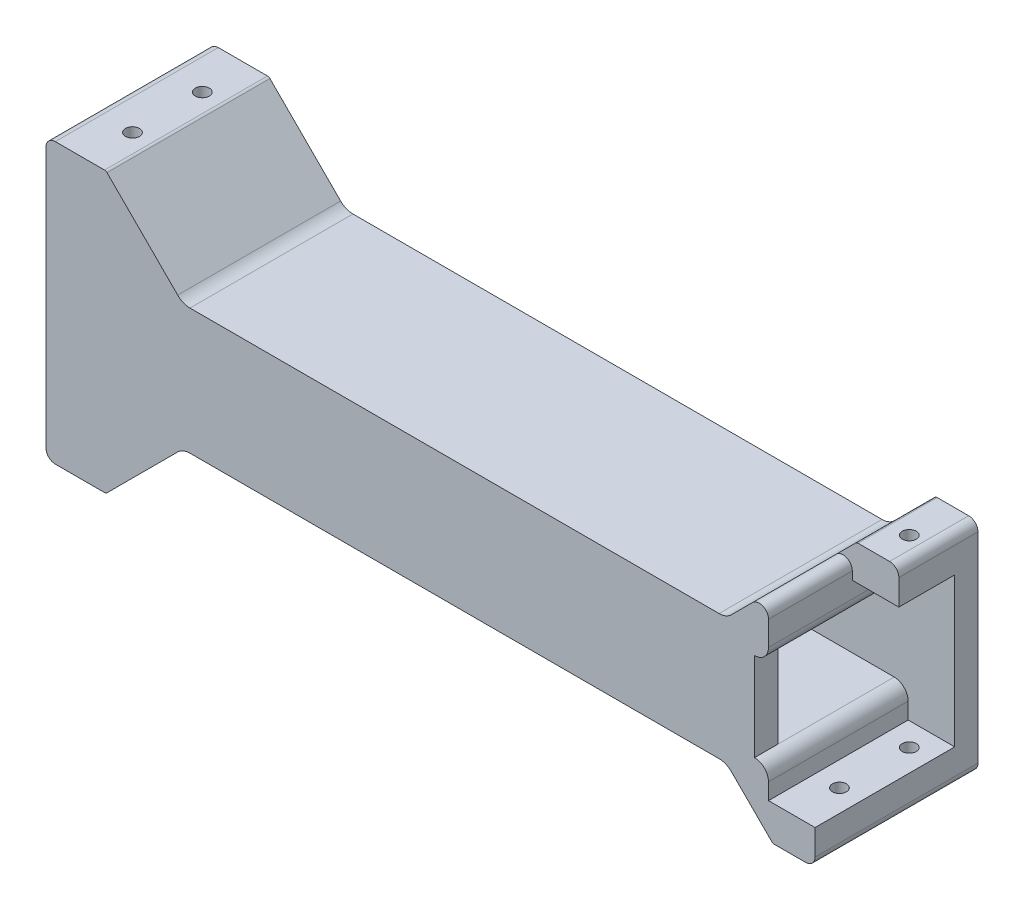
SolidWorks part; units mm, degrees
ref_plane "前视基准面" through (0, 0, 0) normal (0, 0, 1) x (1, 0, 0)
ref_plane "上视基准面" through (0, 0, 0) normal (0, 1, 0) x (1, 0, 0)
ref_plane "右视基准面" through (0, 0, 0) normal (1, 0, 0) x (0, 0, -1)
other "Configuration Table"
sketch "草图1" plane through (0, 0, 0) normal (0, 0, 1) x (1, 0, 0)
  line L43 (27.6425, 62.7843) -> (42.8324, 47.5944)
  line L44 (42.8324, 47.5944) -> (44.9537, 49.7157)
  line L45 (44.9537, 49.7157) -> (29.7639, 64.9056)
  line L46 (27.1217, 66) -> (-22.1169, 66)
  line L47 (-22.1169, 66) -> (-22.1169, 63)
  line L48 (-22.1169, 63) -> (27.1217, 63)
  line L49 (27.1217, 3) -> (-22.1169, 3)
  line L50 (-22.1169, 3) -> (-22.1169, 0)
  line L51 (-22.1169, 0) -> (27.1217, 0)
  line L52 (29.7639, 1.0944) -> (44.9537, 16.2843)
  line L53 (44.9537, 16.2843) -> (42.8324, 18.4056)
  line L54 (42.8324, 18.4056) -> (27.6425, 3.2157)
  line L55 (159.1217, 49.5) -> (45.4745, 49.5)
  line L56 (45.4745, 49.5) -> (45.4745, 46.5)
  line L57 (45.4745, 46.5) -> (159.1217, 46.5)
  line L58 (168.3324, 58.4056) -> (159.6425, 49.7157)
  line L59 (161.7639, 47.5944) -> (170.4537, 56.2843)
  line L60 (170.9745, 56.5) -> (183.3346, 56.5)
  line L61 (183.3346, 56.5) -> (183.3346, 59.5)
  line L62 (183.3346, 59.5) -> (170.9745, 59.5)
  line L63 (170.9745, 6.5) -> (183.3346, 6.5)
  line L64 (183.3346, 6.5) -> (183.3346, 9.5)
  line L65 (183.3346, 9.5) -> (170.9745, 9.5)
  line L66 (159.1217, 19.5) -> (45.4745, 19.5)
  line L67 (45.4745, 19.5) -> (45.4745, 16.5)
  line L68 (45.4745, 16.5) -> (159.1217, 16.5)
  line L69 (170.4537, 9.7157) -> (161.7639, 18.4056)
  line L70 (159.6425, 16.2843) -> (168.3324, 7.5944)
  line L71 (14.5441, 63) -> (14.5441, 3)
  line L72 (179.7384, 56.5) -> (179.7384, 9.5)
  line L79 (168.3324, 7.5944) -> (170.4537, 9.7157)
  line L80 (170.4537, 9.7157) -> (161.7639, 18.4056)
  line L81 (161.7639, 18.4056) -> (159.6425, 16.2843)
  line L82 (159.6425, 16.2843) -> (168.3324, 7.5944)
  arc A14 (27.6425, 62.7843) -> (27.1217, 63) centre (27.1217, 62.2634) ccw
  arc A15 (29.7639, 64.9056) -> (27.1217, 66) centre (27.1217, 62.2634) ccw
  arc A16 (27.1217, 0) -> (29.7639, 1.0944) centre (27.1217, 3.7366) ccw
  arc A17 (27.1217, 3) -> (27.6425, 3.2157) centre (27.1217, 3.7366) ccw
  arc A18 (159.1217, 46.5) -> (161.7639, 47.5944) centre (159.1217, 50.2366) ccw
  arc A19 (159.1217, 49.5) -> (159.6425, 49.7157) centre (159.1217, 50.2366) ccw
  arc A20 (170.9745, 56.5) -> (170.4537, 56.2843) centre (170.9745, 55.7634) ccw
  arc A21 (170.9745, 59.5) -> (168.3324, 58.4056) centre (170.9745, 55.7634) ccw
  arc A22 (168.3324, 7.5944) -> (170.9745, 6.5) centre (170.9745, 10.2366) ccw
  arc A23 (170.4537, 9.7157) -> (170.9745, 9.5) centre (170.9745, 10.2366) ccw
  arc A24 (159.6425, 16.2843) -> (159.1217, 16.5) centre (159.1217, 15.7634) ccw
  arc A25 (161.7639, 18.4056) -> (159.1217, 19.5) centre (159.1217, 15.7634) ccw
  arc A26 (45.4745, 19.5) -> (42.8324, 18.4056) centre (45.4745, 15.7634) ccw
  arc A27 (45.4745, 16.5) -> (44.9537, 16.2843) centre (45.4745, 15.7634) ccw
  arc A28 (45.4745, 49.5) -> (44.9537, 49.7157) centre (45.4745, 50.2366) cw
  arc A29 (45.4745, 46.5) -> (42.8324, 47.5944) centre (45.4745, 50.2366) cw
extrude "凸台-拉伸1" add sketch "草图1" along normal blind 35 contours L57 A29 L43 A14 L48 L71 L49 A17 L54 A26 L66 A25 L69 A23 L65 L72 L60 A20 L59 A18
sketch "草图3" plane through (14.5441, 0, 0) normal (-1, 0, 0) x (0, 0, 1)
  line L0 (35, 46.5) -> (0, 46.5) construction
  line L1 (35, 19.5) -> (0, 19.5) construction
  line L2 (35, 46.5) -> (0, 46.5) construction
  line L3 (35, 19.5) -> (0, 19.5) construction
  line L4 (0, 46.5) -> (35, 19.5) construction
  line L5 (35, 46.5) -> (0, 19.5) construction
  line L6 (35, 63) -> (35, 3) construction
  line L7 (5, 42.5) -> (30, 42.5)
  line L8 (5, 42.5) -> (5, 23.5)
  line L9 (5, 23.5) -> (30, 23.5)
  line L10 (30, 42.5) -> (30, 23.5)
  line L11 (5, 42.5) -> (30, 23.5) construction
  line L12 (5, 23.5) -> (30, 42.5) construction
  point P4 (17.5, 33)
  dimension "D1" = 5
  dimension "D2" = 4
extrude "切除-拉伸1" cut sketch "草图3" against normal through all
sketch "草图4" plane through (14.5441, 0, 0) normal (-1, 0, 0) x (0, 0, 1)
  line L18 (0, 63) -> (0, 3)
  line L19 (0, 3) -> (35, 3)
  line L20 (35, 3) -> (35, 63)
  line L39 (35, 63) -> (0, 63)
  line L40 (0, 63) -> (0, 3)
  line L41 (0, 3) -> (35, 3)
  line L42 (35, 3) -> (35, 63)
  line L43 (35, 63) -> (0, 63)
  line L44 (5, 55) -> (30, 55)
  line L45 (5, 11) -> (30, 11)
  line L48 (5, 58) -> (5, 8)
  line L49 (5, 8) -> (30, 8)
  line L50 (30, 8) -> (30, 58)
  line L51 (30, 58) -> (5, 58)
  line L52 (5, 58) -> (5, 8)
  line L53 (5, 8) -> (30, 8)
  line L54 (30, 8) -> (30, 58)
  line L55 (30, 58) -> (5, 58)
  dimension "D3" = 3
  dimension "D4" = 3
  dimension "D1" = 0
  dimension "D2" = 5
extrude "切除-拉伸2" cut sketch "草图4" against normal blind 13.5
sketch "草图5" plane through (179.7384, 0, 0) normal (1, 0, 0) x (0, 0, -1)
  line L0 (-35, 56.5) -> (0, 9.5) construction
  line L1 (-35, 9.5) -> (0, 56.5) construction
  line L4 (-30, 49) -> (-5, 49)
  line L5 (0, 9.5) -> (0, 56.5)
  line L7 (0, 56.5) -> (-35, 56.5)
  line L16 (-35, 56.5) -> (-35, 9.5)
  line L18 (-35, 9.5) -> (0, 9.5)
  line L19 (0, 9.5) -> (0, 56.5) construction
  line L20 (0, 56.5) -> (-35, 56.5) construction
  line L23 (-35, 56.5) -> (-35, 9.5) construction
  line L24 (-35, 9.5) -> (0, 9.5) construction
  line L25 (-30, 49) -> (-30, 17)
  line L26 (-30, 17) -> (-5, 17)
  line L27 (-5, 49) -> (-5, 17)
  line L28 (-30, 49) -> (-5, 17) construction
  line L29 (-30, 17) -> (-5, 49) construction
  point P2 (-17.5, 33)
  dimension "D2" = 25
  dimension "D3" = 32
  dimension "D1" = 0
extrude "切除-拉伸3" cut sketch "草图5" against normal blind 10
fillet "圆角1" radius 3 4 edges at (169.7384, 23.5, 17.5) (169.7384, 42.5, 17.5) (28.0441, 42.5, 17.5) (28.0441, 23.5, 17.5)
fillet "圆角2" radius 2 4 edges at (179.7384, 56.5, 17.5) (179.7384, 9.5, 17.5) (14.5441, 63, 17.5) (14.5441, 3, 17.5)
sketch "草图6" plane through (0, 55, 0) normal (0, -1, 0) x (1, 0, 0)
  circle A0 centre (23.1217, 25) radius 1.5 construction
  circle A1 centre (23.1217, 25) radius 1.5
  circle A2 centre (23.1217, 10) radius 1.5 construction
  circle A3 centre (23.1217, 10) radius 1.5
extrude "切除-拉伸4" cut sketch "草图6" against normal through all and the other way through all
sketch "草图7" plane through (0, 49, 0) normal (0, -1, 0) x (1, 0, 0)
  circle A0 centre (174.9745, 25) radius 1.5 construction
  circle A1 centre (174.9745, 10) radius 1.5 construction
  circle A2 centre (174.9745, 25) radius 1.5
  circle A3 centre (174.9745, 10) radius 1.5
extrude "切除-拉伸5" cut sketch "草图7" against normal through all and the other way through all
sketch "草图8" plane through (0, 0, 5) normal (0, 0, 1) x (1, 0, 0)
  line L0 (28.0441, 45.5) -> (28.0441, 20.5)
  line L1 (169.7384, 45.5) -> (169.7384, 20.5)
  line L12 (179.7384, 17) -> (179.7384, 49)
  line L13 (179.7384, 49) -> (169.7384, 49)
  line L14 (169.7384, 49) -> (169.7384, 45.5)
  line L15 (166.7384, 42.5) -> (31.0441, 42.5)
  line L16 (28.0441, 45.5) -> (28.0441, 55)
  line L17 (28.0441, 55) -> (14.5441, 55)
  line L18 (14.5441, 55) -> (14.5441, 11)
  line L19 (14.5441, 11) -> (28.0441, 11)
  line L20 (28.0441, 11) -> (28.0441, 20.5)
  line L21 (31.0441, 23.5) -> (166.7384, 23.5)
  line L22 (169.7384, 20.5) -> (169.7384, 17)
  line L23 (169.7384, 17) -> (179.7384, 17)
  line L24 (179.7384, 17) -> (179.7384, 49)
  line L25 (179.7384, 49) -> (169.7384, 49)
  line L26 (169.7384, 49) -> (169.7384, 45.5)
  line L27 (166.7384, 42.5) -> (31.0441, 42.5)
  line L28 (28.0441, 45.5) -> (28.0441, 55)
  line L29 (28.0441, 55) -> (14.5441, 55)
  line L30 (14.5441, 55) -> (14.5441, 11)
  line L31 (14.5441, 11) -> (28.0441, 11)
  line L32 (28.0441, 11) -> (28.0441, 20.5)
  line L33 (31.0441, 23.5) -> (166.7384, 23.5)
  line L34 (169.7384, 20.5) -> (169.7384, 17)
  line L35 (169.7384, 17) -> (179.7384, 17)
  arc A4 (166.7384, 42.5) -> (169.7384, 45.5) centre (166.7384, 45.5) ccw
  arc A5 (28.0441, 45.5) -> (31.0441, 42.5) centre (31.0441, 45.5) ccw
  arc A6 (31.0441, 23.5) -> (28.0441, 20.5) centre (31.0441, 20.5) ccw
  arc A7 (169.7384, 20.5) -> (166.7384, 23.5) centre (166.7384, 20.5) ccw
  arc A8 (166.7384, 42.5) -> (169.7384, 45.5) centre (166.7384, 45.5) ccw
  arc A9 (28.0441, 45.5) -> (31.0441, 42.5) centre (31.0441, 45.5) ccw
  arc A10 (31.0441, 23.5) -> (28.0441, 20.5) centre (31.0441, 20.5) ccw
  arc A11 (169.7384, 20.5) -> (166.7384, 23.5) centre (166.7384, 20.5) ccw
  dimension "D1" = 0
extrude "切除-拉伸6" cut sketch "草图8" against normal through all
sketch "草图9" plane through (0, 0, 30) normal (0, 0, -1) x (-1, 0, 0)
  line L0 (-179.7384, 49) -> (-179.7384, 17)
  line L20 (-179.7384, 54.5) -> (-179.7384, 49)
  line L21 (-179.7384, 49) -> (-169.7384, 49)
  line L22 (-169.7384, 49) -> (-169.7384, 17)
  line L23 (-169.7384, 17) -> (-179.7384, 17)
  line L24 (-179.7384, 17) -> (-179.7384, 11.5)
  line L25 (-177.7384, 9.5) -> (-170.9745, 9.5)
  line L26 (-170.4537, 9.7157) -> (-161.7639, 18.4056)
  line L27 (-159.1217, 19.5) -> (-45.4745, 19.5)
  line L28 (-42.8324, 18.4056) -> (-27.6425, 3.2157)
  line L29 (-27.1217, 3) -> (-16.5441, 3)
  line L30 (-14.5441, 5) -> (-14.5441, 11)
  line L31 (-14.5441, 11) -> (-28.0441, 11)
  line L32 (-28.0441, 11) -> (-28.0441, 55)
  line L33 (-28.0441, 55) -> (-14.5441, 55)
  line L34 (-14.5441, 55) -> (-14.5441, 61)
  line L35 (-16.5441, 63) -> (-27.1217, 63)
  line L36 (-27.6425, 62.7843) -> (-42.8324, 47.5944)
  line L37 (-45.4745, 46.5) -> (-159.1217, 46.5)
  line L38 (-161.7639, 47.5944) -> (-170.4537, 56.2843)
  line L39 (-170.9745, 56.5) -> (-177.7384, 56.5)
  line L40 (-179.7384, 54.5) -> (-179.7384, 49)
  line L41 (-179.7384, 49) -> (-169.7384, 49)
  line L42 (-169.7384, 49) -> (-169.7384, 17)
  line L43 (-169.7384, 17) -> (-179.7384, 17)
  line L44 (-179.7384, 17) -> (-179.7384, 11.5)
  line L45 (-177.7384, 9.5) -> (-170.9745, 9.5)
  line L46 (-170.4537, 9.7157) -> (-161.7639, 18.4056)
  line L47 (-159.1217, 19.5) -> (-45.4745, 19.5)
  line L48 (-42.8324, 18.4056) -> (-27.6425, 3.2157)
  line L49 (-27.1217, 3) -> (-16.5441, 3)
  line L50 (-14.5441, 5) -> (-14.5441, 11)
  line L51 (-14.5441, 11) -> (-28.0441, 11)
  line L52 (-28.0441, 11) -> (-28.0441, 55)
  line L53 (-28.0441, 55) -> (-14.5441, 55)
  line L54 (-14.5441, 55) -> (-14.5441, 61)
  line L55 (-16.5441, 63) -> (-27.1217, 63)
  line L56 (-27.6425, 62.7843) -> (-42.8324, 47.5944)
  line L57 (-45.4745, 46.5) -> (-159.1217, 46.5)
  line L58 (-161.7639, 47.5944) -> (-170.4537, 56.2843)
  line L59 (-170.9745, 56.5) -> (-177.7384, 56.5)
  arc A12 (-179.7384, 11.5) -> (-177.7384, 9.5) centre (-177.7384, 11.5) ccw
  arc A13 (-170.9745, 9.5) -> (-170.4537, 9.7157) centre (-170.9745, 10.2366) ccw
  arc A14 (-159.1217, 19.5) -> (-161.7639, 18.4056) centre (-159.1217, 15.7634) ccw
  arc A15 (-42.8324, 18.4056) -> (-45.4745, 19.5) centre (-45.4745, 15.7634) ccw
  arc A16 (-27.6425, 3.2157) -> (-27.1217, 3) centre (-27.1217, 3.7366) ccw
  arc A17 (-16.5441, 3) -> (-14.5441, 5) centre (-16.5441, 5) ccw
  arc A18 (-14.5441, 61) -> (-16.5441, 63) centre (-16.5441, 61) ccw
  arc A19 (-27.1217, 63) -> (-27.6425, 62.7843) centre (-27.1217, 62.2634) ccw
  arc A20 (-45.4745, 46.5) -> (-42.8324, 47.5944) centre (-45.4745, 50.2366) ccw
  arc A21 (-161.7639, 47.5944) -> (-159.1217, 46.5) centre (-159.1217, 50.2366) ccw
  arc A22 (-170.4537, 56.2843) -> (-170.9745, 56.5) centre (-170.9745, 55.7634) ccw
  arc A23 (-177.7384, 56.5) -> (-179.7384, 54.5) centre (-177.7384, 54.5) ccw
  arc A24 (-179.7384, 11.5) -> (-177.7384, 9.5) centre (-177.7384, 11.5) ccw
  arc A25 (-170.9745, 9.5) -> (-170.4537, 9.7157) centre (-170.9745, 10.2366) ccw
  arc A26 (-159.1217, 19.5) -> (-161.7639, 18.4056) centre (-159.1217, 15.7634) ccw
  arc A27 (-42.8324, 18.4056) -> (-45.4745, 19.5) centre (-45.4745, 15.7634) ccw
  arc A28 (-27.6425, 3.2157) -> (-27.1217, 3) centre (-27.1217, 3.7366) ccw
  arc A29 (-16.5441, 3) -> (-14.5441, 5) centre (-16.5441, 5) ccw
  arc A30 (-14.5441, 61) -> (-16.5441, 63) centre (-16.5441, 61) ccw
  arc A31 (-27.1217, 63) -> (-27.6425, 62.7843) centre (-27.1217, 62.2634) ccw
  arc A32 (-45.4745, 46.5) -> (-42.8324, 47.5944) centre (-45.4745, 50.2366) ccw
  arc A33 (-161.7639, 47.5944) -> (-159.1217, 46.5) centre (-159.1217, 50.2366) ccw
  arc A34 (-170.4537, 56.2843) -> (-170.9745, 56.5) centre (-170.9745, 55.7634) ccw
  arc A35 (-177.7384, 56.5) -> (-179.7384, 54.5) centre (-177.7384, 54.5) ccw
  line M33 (-179.7384, 49) -> (-179.7384, 17)
  line M34 (-179.7384, 17) -> (-169.7384, 17)
  line M35 (-169.7384, 17) -> (-169.7384, 20.5)
  line M47 (-169.7384, 45.5) -> (-169.7384, 49)
  line M48 (-169.7384, 49) -> (-179.7384, 49)
  dimension "D1" = 0
extrude "切除-拉伸7" cut sketch "草图9" against normal blind 10 contours L42 M47 M48 M33 M34 M35
sketch "草图10" plane through (0, 0, 35) normal (0, 0, 1) x (1, 0, 0)
  line L0 (169.7384, 49) -> (169.7384, 55.569)
  line L16 (179.7384, 17) -> (169.7384, 17)
  line L17 (169.7384, 17) -> (169.7384, 49)
  line L18 (169.7384, 49) -> (179.7384, 49)
  line L19 (179.7384, 49) -> (179.7384, 54.5)
  line L20 (177.7384, 56.5) -> (170.9745, 56.5)
  line L21 (170.4537, 56.2843) -> (161.7639, 47.5944)
  line L22 (159.1217, 46.5) -> (45.4745, 46.5)
  line L23 (42.8324, 47.5944) -> (27.6425, 62.7843)
  line L24 (27.1217, 63) -> (16.5441, 63)
  line L25 (14.5441, 61) -> (14.5441, 5)
  line L26 (16.5441, 3) -> (27.1217, 3)
  line L27 (27.6425, 3.2157) -> (42.8324, 18.4056)
  line L28 (45.4745, 19.5) -> (159.1217, 19.5)
  line L29 (161.7639, 18.4056) -> (170.4537, 9.7157)
  line L30 (170.9745, 9.5) -> (177.7384, 9.5)
  line L31 (179.7384, 11.5) -> (179.7384, 17)
  line L32 (179.7384, 17) -> (169.7384, 17)
  line L33 (169.7384, 17) -> (169.7384, 49)
  line L34 (169.7384, 49) -> (179.7384, 49)
  line L35 (179.7384, 49) -> (179.7384, 54.5)
  line L36 (177.7384, 56.5) -> (170.9745, 56.5)
  line L37 (170.4537, 56.2843) -> (161.7639, 47.5944)
  line L38 (159.1217, 46.5) -> (45.4745, 46.5)
  line L39 (42.8324, 47.5944) -> (27.6425, 62.7843)
  line L40 (27.1217, 63) -> (16.5441, 63)
  line L41 (14.5441, 61) -> (14.5441, 5)
  line L42 (16.5441, 3) -> (27.1217, 3)
  line L43 (27.6425, 3.2157) -> (42.8324, 18.4056)
  line L44 (45.4745, 19.5) -> (159.1217, 19.5)
  line L45 (161.7639, 18.4056) -> (170.4537, 9.7157)
  line L46 (170.9745, 9.5) -> (177.7384, 9.5)
  line L47 (179.7384, 11.5) -> (179.7384, 17)
  arc A12 (179.7384, 54.5) -> (177.7384, 56.5) centre (177.7384, 54.5) ccw
  arc A13 (170.9745, 56.5) -> (170.4537, 56.2843) centre (170.9745, 55.7634) ccw
  arc A14 (159.1217, 46.5) -> (161.7639, 47.5944) centre (159.1217, 50.2366) ccw
  arc A15 (42.8324, 47.5944) -> (45.4745, 46.5) centre (45.4745, 50.2366) ccw
  arc A16 (27.6425, 62.7843) -> (27.1217, 63) centre (27.1217, 62.2634) ccw
  arc A17 (16.5441, 63) -> (14.5441, 61) centre (16.5441, 61) ccw
  arc A18 (14.5441, 5) -> (16.5441, 3) centre (16.5441, 5) ccw
  arc A19 (27.1217, 3) -> (27.6425, 3.2157) centre (27.1217, 3.7366) ccw
  arc A20 (45.4745, 19.5) -> (42.8324, 18.4056) centre (45.4745, 15.7634) ccw
  arc A21 (161.7639, 18.4056) -> (159.1217, 19.5) centre (159.1217, 15.7634) ccw
  arc A22 (170.4537, 9.7157) -> (170.9745, 9.5) centre (170.9745, 10.2366) ccw
  arc A23 (177.7384, 9.5) -> (179.7384, 11.5) centre (177.7384, 11.5) ccw
  arc A24 (179.7384, 54.5) -> (177.7384, 56.5) centre (177.7384, 54.5) ccw
  arc A25 (170.9745, 56.5) -> (170.4537, 56.2843) centre (170.9745, 55.7634) ccw
  arc A26 (159.1217, 46.5) -> (161.7639, 47.5944) centre (159.1217, 50.2366) ccw
  arc A27 (42.8324, 47.5944) -> (45.4745, 46.5) centre (45.4745, 50.2366) ccw
  arc A28 (27.6425, 62.7843) -> (27.1217, 63) centre (27.1217, 62.2634) ccw
  arc A29 (16.5441, 63) -> (14.5441, 61) centre (16.5441, 61) ccw
  arc A30 (14.5441, 5) -> (16.5441, 3) centre (16.5441, 5) ccw
  arc A31 (27.1217, 3) -> (27.6425, 3.2157) centre (27.1217, 3.7366) ccw
  arc A32 (45.4745, 19.5) -> (42.8324, 18.4056) centre (45.4745, 15.7634) ccw
  arc A33 (161.7639, 18.4056) -> (159.1217, 19.5) centre (159.1217, 15.7634) ccw
  arc A34 (170.4537, 9.7157) -> (170.9745, 9.5) centre (170.9745, 10.2366) ccw
  arc A35 (177.7384, 9.5) -> (179.7384, 11.5) centre (177.7384, 11.5) ccw
  line M31 (169.7384, 49) -> (179.7384, 49)
  line M32 (179.7384, 49) -> (179.7384, 54.5)
  arc M33 (179.7384, 54.5) -> (177.7384, 56.5) centre (177.7384, 54.5) ccw
  line M34 (177.7384, 56.5) -> (170.9745, 56.5)
  arc M35 (170.9745, 56.5) -> (170.4537, 56.2843) centre (170.9745, 55.7634) ccw
  line M36 (170.4537, 56.2843) -> (161.7639, 47.5944)
  dimension "D1" = 0
extrude "切除-拉伸8" cut sketch "草图10" against normal blind 18 contours L0 M31 M32 M33 M34 M35 M36
fillet "圆角3" radius 2 1 edges at (169.7384, 55.569, 26)
sketch "草图11" plane through (0, 0, 0) normal (0, 0, -1) x (-1, 0, 0)
  line L0 (-179.7384, 49) -> (-179.7384, 17)
  line L20 (-179.7384, 54.5) -> (-179.7384, 49)
  line L21 (-179.7384, 49) -> (-169.7384, 49)
  line L22 (-169.7384, 49) -> (-169.7384, 17)
  line L23 (-169.7384, 17) -> (-179.7384, 17)
  line L24 (-179.7384, 17) -> (-179.7384, 11.5)
  line L25 (-177.7384, 9.5) -> (-170.9745, 9.5)
  line L26 (-170.4537, 9.7157) -> (-161.7639, 18.4056)
  line L27 (-159.1217, 19.5) -> (-45.4745, 19.5)
  line L28 (-42.8324, 18.4056) -> (-27.6425, 3.2157)
  line L29 (-27.1217, 3) -> (-16.5441, 3)
  line L30 (-14.5441, 5) -> (-14.5441, 11)
  line L31 (-14.5441, 11) -> (-28.0441, 11)
  line L32 (-28.0441, 11) -> (-28.0441, 55)
  line L33 (-28.0441, 55) -> (-14.5441, 55)
  line L34 (-14.5441, 55) -> (-14.5441, 61)
  line L35 (-16.5441, 63) -> (-27.1217, 63)
  line L36 (-27.6425, 62.7843) -> (-42.8324, 47.5944)
  line L37 (-45.4745, 46.5) -> (-159.1217, 46.5)
  line L38 (-161.7639, 47.5944) -> (-170.4537, 56.2843)
  line L39 (-170.9745, 56.5) -> (-177.7384, 56.5)
  line L40 (-179.7384, 54.5) -> (-179.7384, 49)
  line L41 (-179.7384, 49) -> (-169.7384, 49)
  line L42 (-169.7384, 49) -> (-169.7384, 17)
  line L43 (-169.7384, 17) -> (-179.7384, 17)
  line L44 (-179.7384, 17) -> (-179.7384, 11.5)
  line L45 (-177.7384, 9.5) -> (-170.9745, 9.5)
  line L46 (-170.4537, 9.7157) -> (-161.7639, 18.4056)
  line L47 (-159.1217, 19.5) -> (-45.4745, 19.5)
  line L48 (-42.8324, 18.4056) -> (-27.6425, 3.2157)
  line L49 (-27.1217, 3) -> (-16.5441, 3)
  line L50 (-14.5441, 5) -> (-14.5441, 11)
  line L51 (-14.5441, 11) -> (-28.0441, 11)
  line L52 (-28.0441, 11) -> (-28.0441, 55)
  line L53 (-28.0441, 55) -> (-14.5441, 55)
  line L54 (-14.5441, 55) -> (-14.5441, 61)
  line L55 (-16.5441, 63) -> (-27.1217, 63)
  line L56 (-27.6425, 62.7843) -> (-42.8324, 47.5944)
  line L57 (-45.4745, 46.5) -> (-159.1217, 46.5)
  line L58 (-161.7639, 47.5944) -> (-170.4537, 56.2843)
  line L59 (-170.9745, 56.5) -> (-177.7384, 56.5)
  arc A12 (-179.7384, 11.5) -> (-177.7384, 9.5) centre (-177.7384, 11.5) ccw
  arc A13 (-170.9745, 9.5) -> (-170.4537, 9.7157) centre (-170.9745, 10.2366) ccw
  arc A14 (-159.1217, 19.5) -> (-161.7639, 18.4056) centre (-159.1217, 15.7634) ccw
  arc A15 (-42.8324, 18.4056) -> (-45.4745, 19.5) centre (-45.4745, 15.7634) ccw
  arc A16 (-27.6425, 3.2157) -> (-27.1217, 3) centre (-27.1217, 3.7366) ccw
  arc A17 (-16.5441, 3) -> (-14.5441, 5) centre (-16.5441, 5) ccw
  arc A18 (-14.5441, 61) -> (-16.5441, 63) centre (-16.5441, 61) ccw
  arc A19 (-27.1217, 63) -> (-27.6425, 62.7843) centre (-27.1217, 62.2634) ccw
  arc A20 (-45.4745, 46.5) -> (-42.8324, 47.5944) centre (-45.4745, 50.2366) ccw
  arc A21 (-161.7639, 47.5944) -> (-159.1217, 46.5) centre (-159.1217, 50.2366) ccw
  arc A22 (-170.4537, 56.2843) -> (-170.9745, 56.5) centre (-170.9745, 55.7634) ccw
  arc A23 (-177.7384, 56.5) -> (-179.7384, 54.5) centre (-177.7384, 54.5) ccw
  arc A24 (-179.7384, 11.5) -> (-177.7384, 9.5) centre (-177.7384, 11.5) ccw
  arc A25 (-170.9745, 9.5) -> (-170.4537, 9.7157) centre (-170.9745, 10.2366) ccw
  arc A26 (-159.1217, 19.5) -> (-161.7639, 18.4056) centre (-159.1217, 15.7634) ccw
  arc A27 (-42.8324, 18.4056) -> (-45.4745, 19.5) centre (-45.4745, 15.7634) ccw
  arc A28 (-27.6425, 3.2157) -> (-27.1217, 3) centre (-27.1217, 3.7366) ccw
  arc A29 (-16.5441, 3) -> (-14.5441, 5) centre (-16.5441, 5) ccw
  arc A30 (-14.5441, 61) -> (-16.5441, 63) centre (-16.5441, 61) ccw
  arc A31 (-27.1217, 63) -> (-27.6425, 62.7843) centre (-27.1217, 62.2634) ccw
  arc A32 (-45.4745, 46.5) -> (-42.8324, 47.5944) centre (-45.4745, 50.2366) ccw
  arc A33 (-161.7639, 47.5944) -> (-159.1217, 46.5) centre (-159.1217, 50.2366) ccw
  arc A34 (-170.4537, 56.2843) -> (-170.9745, 56.5) centre (-170.9745, 55.7634) ccw
  arc A35 (-177.7384, 56.5) -> (-179.7384, 54.5) centre (-177.7384, 54.5) ccw
  line M34 (-179.7384, 49) -> (-169.7384, 49)
  line M35 (-169.7384, 49) -> (-169.7384, 17)
  line M36 (-169.7384, 17) -> (-179.7384, 17)
  dimension "D1" = 0
extrude "凸台-拉伸2" add sketch "草图11" against normal blind 5 contours L0 M34 M36 M35
sketch "草图12" plane through (0, 0, 30) normal (0, 0, -1) x (-1, 0, 0)
  line L0 (-166.7384, 42.5) -> (-166.7384, 23.5)
  line L8 (-169.7384, 45.5) -> (-169.7384, 20.5)
  line L9 (-166.7384, 23.5) -> (-31.0441, 23.5)
  line L10 (-28.0441, 20.5) -> (-28.0441, 11)
  line L11 (-28.0441, 11) -> (-14.5441, 11)
  line L12 (-14.5441, 11) -> (-14.5441, 55)
  line L13 (-14.5441, 55) -> (-28.0441, 55)
  line L14 (-28.0441, 55) -> (-28.0441, 45.5)
  line L15 (-31.0441, 42.5) -> (-166.7384, 42.5)
  line L16 (-169.7384, 45.5) -> (-169.7384, 20.5)
  line L17 (-166.7384, 23.5) -> (-31.0441, 23.5)
  line L18 (-28.0441, 20.5) -> (-28.0441, 11)
  line L19 (-28.0441, 11) -> (-14.5441, 11)
  line L20 (-14.5441, 11) -> (-14.5441, 55)
  line L21 (-14.5441, 55) -> (-28.0441, 55)
  line L22 (-28.0441, 55) -> (-28.0441, 45.5)
  line L23 (-31.0441, 42.5) -> (-166.7384, 42.5)
  arc A4 (-166.7384, 23.5) -> (-169.7384, 20.5) centre (-166.7384, 20.5) ccw
  arc A5 (-28.0441, 20.5) -> (-31.0441, 23.5) centre (-31.0441, 20.5) ccw
  arc A6 (-31.0441, 42.5) -> (-28.0441, 45.5) centre (-31.0441, 45.5) ccw
  arc A7 (-169.7384, 45.5) -> (-166.7384, 42.5) centre (-166.7384, 45.5) ccw
  arc A8 (-166.7384, 23.5) -> (-169.7384, 20.5) centre (-166.7384, 20.5) ccw
  arc A9 (-28.0441, 20.5) -> (-31.0441, 23.5) centre (-31.0441, 20.5) ccw
  arc A10 (-31.0441, 42.5) -> (-28.0441, 45.5) centre (-31.0441, 45.5) ccw
  arc A11 (-169.7384, 45.5) -> (-166.7384, 42.5) centre (-166.7384, 45.5) ccw
  dimension "D1" = 0
extrude "切除-拉伸10" cut sketch "草图12" against normal blind 5 contours L0 A6 L8
